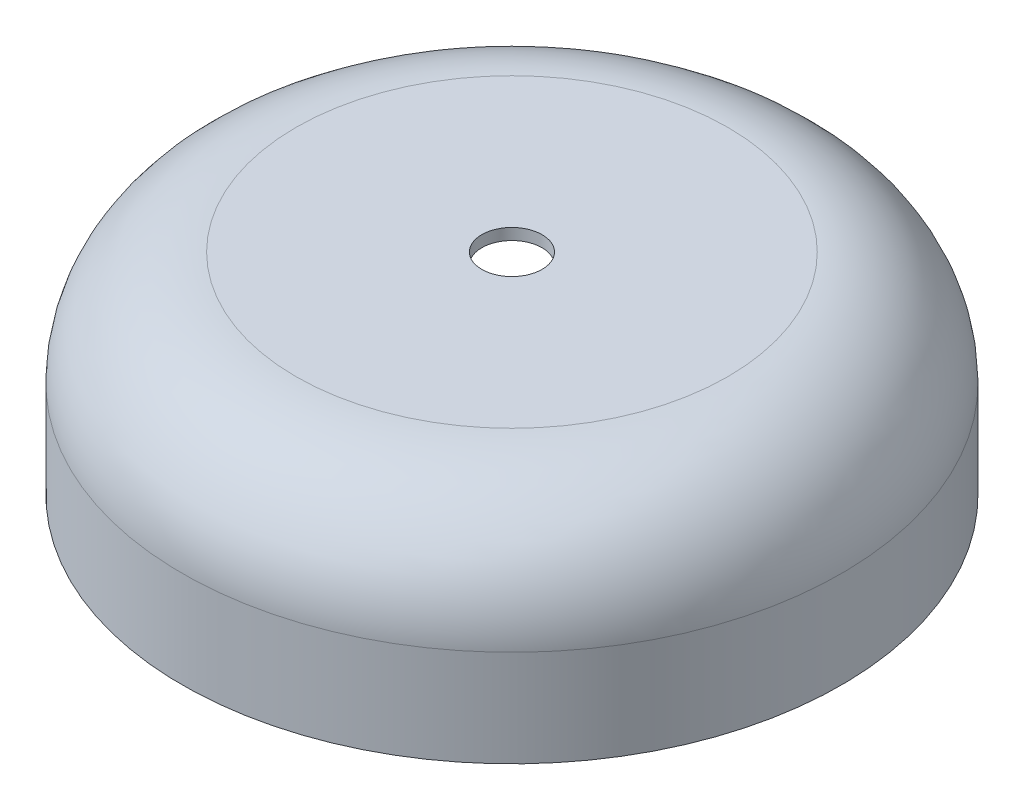
SolidWorks part; units mm, degrees
ref_plane "Front Plane" through (0, 0, 0) normal (0, 0, 1) x (1, 0, 0)
ref_plane "Top Plane" through (0, 0, 0) normal (0, 1, 0) x (1, 0, 0)
ref_plane "Right Plane" through (0, 0, 0) normal (1, 0, 0) x (0, 0, -1)
sketch "Sketch1" plane through (0, 0, 0) normal (0, 0, 1) x (1, 0, 0)
  line L0 (0, 0) -> (0, 18.5) construction
  line L1 (0, 18.5) -> (-19, 18.5)
  line L2 (-29, 8.5) -> (-29, 0)
  arc A0 (-19, 18.5) -> (-29, 8.5) centre (-19, 8.5) ccw
  dimension "D1" = 10
  dimension "D2" = 58
  dimension "D3" = 18.5
revolve "Revolve-Thin1" add sketch "Sketch1" angle 360 about L0 wall 1
sketch "Sketch2" plane through (0, 18.5, 0) normal (0, 1, 0) x (1, 0, 0)
  circle A0 centre (0, 0) radius 2.65
  dimension "D1" = 5.3
extrude "Cut-Extrude1" cut sketch "Sketch2" against normal through all
